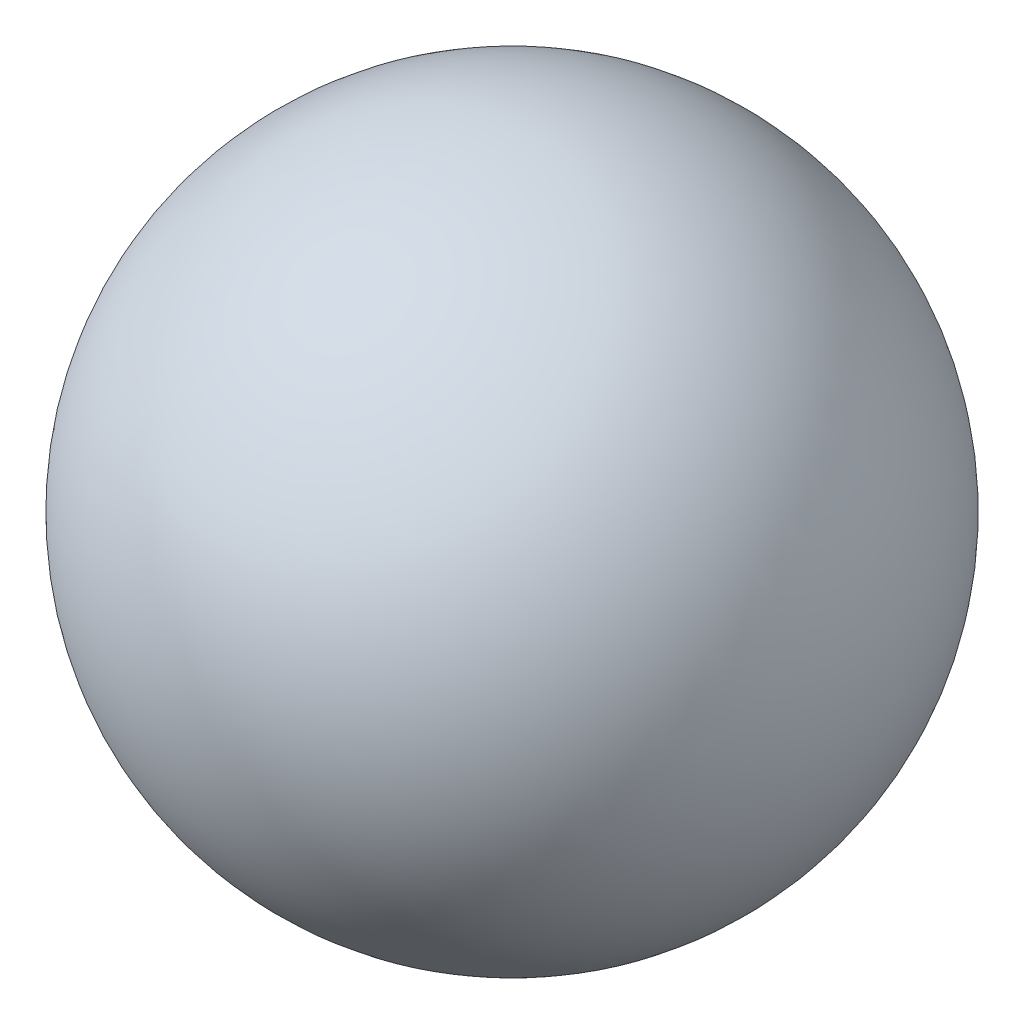
SolidWorks part; units mm, degrees
material "201.0-T6 Insulated Mold Casting (SS)"
ref_plane "Front Plane" through (0, 0, 0) normal (0, 0, 1) x (1, 0, 0)
ref_plane "Top Plane" through (0, 0, 0) normal (0, 1, 0) x (1, 0, 0)
ref_plane "Right Plane" through (0, 0, 0) normal (1, 0, 0) x (0, 0, -1)
sketch "Sketch1" plane through (0, 0, 0) normal (0, 0, 1) x (1, 0, 0)
  line L0 (0, 4.7625) -> (0, -4.7625)
  arc A0 (0, 4.7625) -> (0, -4.7625) centre (0, 0) cw
  dimension "D1" = 9.525
revolve "Revolve1" add sketch "Sketch1" angle 360 about L0
